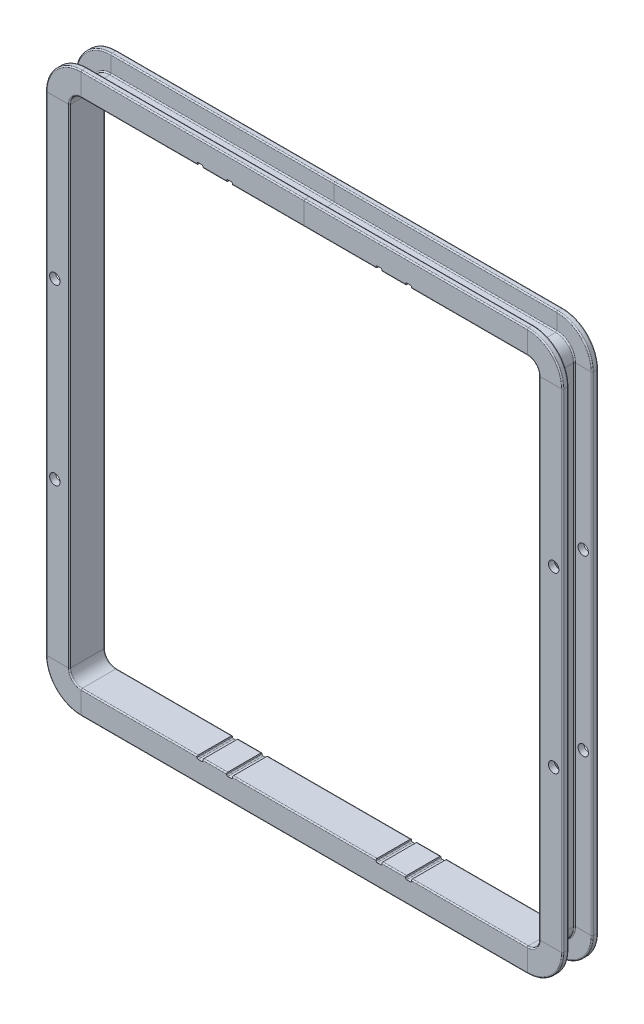
SolidWorks part; units mm, degrees
material "ABS"
ref_plane "Front Plane" through (0, 0, 0) normal (0, 0, 1) x (1, 0, 0)
ref_plane "Top Plane" through (0, 0, 0) normal (0, 1, 0) x (1, 0, 0)
ref_plane "Right Plane" through (0, 0, 0) normal (1, 0, 0) x (0, 0, -1)
sketch "Sketch2" plane through (0, 0, 0) normal (0, 0, 1) x (1, 0, 0)
  line L4 (-886.8198, 967.5698) -> (886.8198, -967.5698) construction
  line L5 (855, 980.75) -> (-855, 980.75)
  line L6 (900, 935.75) -> (900, -935.75)
  line L7 (855, -980.75) -> (-855, -980.75)
  line L8 (-900, 935.75) -> (-900, -935.75)
  line L9 (-886.8198, -967.5698) -> (886.8198, 967.5698) construction
  arc A0 (-855, -980.75) -> (-900, -935.75) centre (-855, -935.75) cw
  arc A1 (900, -935.75) -> (855, -980.75) centre (855, -935.75) cw
  arc A2 (855, 980.75) -> (900, 935.75) centre (855, 935.75) cw
  arc A3 (-855, 980.75) -> (-900, 935.75) centre (-855, 935.75) ccw
  point P0 (0, 0)
  point P18 (0, 0)
  point P20 (855, 980.75)
  dimension "D2" = 45
  dimension "D3" = 1800
  dimension "D1" = 1961.5
sketch "Sketch3" plane through (0, 0, 0) normal (1, 0, 0) x (0, 0, -1)
  line L1 (0, 980.75) -> (0, 935.75) construction
  line L2 (-63.525, 980.75) -> (63.525, 980.75)
  line L3 (68.0625, 985.2875) -> (68.0625, 1066.9625)
  line L5 (-45.375, 1066.9625) -> (-45.375, 1007.975)
  line L6 (-40.8375, 1003.4375) -> (40.8375, 1003.4375)
  line L7 (45.375, 1007.975) -> (45.375, 1066.9625)
  line L9 (-68.0625, 1066.9625) -> (-68.0625, 985.2875)
  line L10 (-49.9125, 1071.5) -> (-63.525, 1071.5)
  line L11 (49.9125, 1071.5) -> (63.525, 1071.5)
  arc A0 (-63.525, 980.75) -> (-68.0625, 985.2875) centre (-63.525, 985.2875) cw
  arc A1 (63.525, 980.75) -> (68.0625, 985.2875) centre (63.525, 985.2875) ccw
  arc A2 (68.0625, 1066.9625) -> (63.525, 1071.5) centre (63.525, 1066.9625) ccw
  arc A3 (45.375, 1066.9625) -> (49.9125, 1071.5) centre (49.9125, 1066.9625) cw
  arc A4 (40.8375, 1003.4375) -> (45.375, 1007.975) centre (40.8375, 1007.975) ccw
  arc A5 (-45.375, 1007.975) -> (-40.8375, 1003.4375) centre (-40.8375, 1007.975) ccw
  arc A6 (-49.9125, 1071.5) -> (-45.375, 1066.9625) centre (-49.9125, 1066.9625) cw
  arc A7 (-63.525, 1071.5) -> (-68.0625, 1066.9625) centre (-63.525, 1066.9625) ccw
  point P0 (0, 980.75)
  point P11 (0, 980.75)
  point P23 (68.0625, 980.75)
  point P26 (68.0625, 1071.5)
  point P29 (45.375, 1071.5)
  point P32 (45.375, 1003.4375)
  point P35 (-45.375, 1003.4375)
  dimension "D5" = 4.5375
  dimension "D2" = 22.6875
  dimension "D1" = 90.75
  dimension "D3" = 22.6875
  dimension "D4" = 90.75
sweep "Sweep1" add profiles "Sketch3" path "Sketch2"
sketch "Sketch5" plane through (0, 0, 0) normal (0, 0, 1) x (1, 0, 0)
  line L0 (-406.5875, 990.75) -> (-392.975, 990.75)
  line L1 (-1216.9089, 0) -> (1386.2762, 0) construction
  line L2 (-388.4375, 986.2125) -> (-388.4375, -986.2125)
  line L4 (-388.4375, 0) -> (-411.125, 0)
  line L5 (-411.125, -986.2125) -> (-411.125, 986.2125)
  line L6 (-406.5875, 990.75) -> (-406.5875, 855) construction
  line L7 (-392.975, 990.75) -> (-392.975, 855) construction
  line L9 (-406.5875, -990.75) -> (-392.975, -990.75)
  line L10 (-343.0625, 922.6875) -> (-343.0625, 801.5742) construction
  line L11 (-302.225, 922.6875) -> (-383.9, 922.6875) construction
  line L12 (-279.5375, -990.75) -> (-293.15, -990.75)
  line L13 (-275, -986.2125) -> (-275, 986.2125)
  line L14 (-297.6875, 0) -> (-275, 0)
  line L15 (-297.6875, 986.2125) -> (-297.6875, -986.2125)
  line L16 (-279.5375, 990.75) -> (-293.15, 990.75)
  line L17 (0, 1301.3162) -> (0, -1456.5953) construction
  line L18 (-406.5875, 990.75) -> (-392.975, 990.75)
  line L19 (-388.4375, 986.2125) -> (-388.4375, -986.2125)
  line L20 (-388.4375, 0) -> (-411.125, 0)
  line L21 (-411.125, -986.2125) -> (-411.125, 986.2125)
  line L22 (-406.5875, -990.75) -> (-392.975, -990.75)
  line L23 (-279.5375, -990.75) -> (-293.15, -990.75)
  line L24 (-275, -986.2125) -> (-275, 986.2125)
  line L25 (-297.6875, 0) -> (-275, 0)
  line L26 (-297.6875, 986.2125) -> (-297.6875, -986.2125)
  line L27 (-279.5375, 990.75) -> (-293.15, 990.75)
  line L28 (343.0625, 922.6875) -> (343.0625, 801.5742) construction
  line L29 (279.5375, 990.75) -> (293.15, 990.75)
  line L30 (297.6875, 986.2125) -> (297.6875, -986.2125)
  line L31 (297.6875, 0) -> (275, 0)
  line L32 (275, -986.2125) -> (275, 986.2125)
  line L33 (279.5375, -990.75) -> (293.15, -990.75)
  line L34 (406.5875, -990.75) -> (392.975, -990.75)
  line L35 (411.125, -986.2125) -> (411.125, 986.2125)
  line L36 (388.4375, 0) -> (411.125, 0)
  line L37 (388.4375, 986.2125) -> (388.4375, -986.2125)
  line L38 (406.5875, 990.75) -> (392.975, 990.75)
  line L39 (279.5375, 990.75) -> (293.15, 990.75)
  line L40 (297.6875, 986.2125) -> (297.6875, -986.2125)
  line L41 (297.6875, 0) -> (275, 0)
  line L42 (275, -986.2125) -> (275, 986.2125)
  line L43 (279.5375, -990.75) -> (293.15, -990.75)
  line L44 (406.5875, -990.75) -> (392.975, -990.75)
  line L45 (411.125, -986.2125) -> (411.125, 986.2125)
  line L46 (388.4375, 0) -> (411.125, 0)
  line L47 (388.4375, 986.2125) -> (388.4375, -986.2125)
  line L48 (406.5875, 990.75) -> (392.975, 990.75)
  line L50 (-855, 980.75) -> (0, 980.75) construction
  arc A0 (-392.975, 990.75) -> (-388.4375, 986.2125) centre (-392.975, 986.2125) cw
  arc A1 (-411.125, 986.2125) -> (-406.5875, 990.75) centre (-406.5875, 986.2125) cw
  arc A2 (-406.5875, 990.75) -> (-411.125, 986.2125) centre (-406.5875, 986.2125) ccw construction
  arc A3 (-411.125, -986.2125) -> (-406.5875, -990.75) centre (-406.5875, -986.2125) ccw
  arc A4 (-392.975, -990.75) -> (-388.4375, -986.2125) centre (-392.975, -986.2125) ccw
  arc A5 (-293.15, -990.75) -> (-297.6875, -986.2125) centre (-293.15, -986.2125) cw
  arc A6 (-275, -986.2125) -> (-279.5375, -990.75) centre (-279.5375, -986.2125) cw
  arc A7 (-275, 986.2125) -> (-279.5375, 990.75) centre (-279.5375, 986.2125) ccw
  arc A8 (-293.15, 990.75) -> (-297.6875, 986.2125) centre (-293.15, 986.2125) ccw
  arc A9 (-392.975, 990.75) -> (-388.4375, 986.2125) centre (-392.975, 986.2125) cw
  arc A10 (-411.125, 986.2125) -> (-406.5875, 990.75) centre (-406.5875, 986.2125) cw
  arc A11 (-411.125, -986.2125) -> (-406.5875, -990.75) centre (-406.5875, -986.2125) ccw
  arc A12 (-392.975, -990.75) -> (-388.4375, -986.2125) centre (-392.975, -986.2125) ccw
  arc A13 (-293.15, -990.75) -> (-297.6875, -986.2125) centre (-293.15, -986.2125) cw
  arc A14 (-275, -986.2125) -> (-279.5375, -990.75) centre (-279.5375, -986.2125) cw
  arc A15 (-275, 986.2125) -> (-279.5375, 990.75) centre (-279.5375, 986.2125) ccw
  arc A16 (-293.15, 990.75) -> (-297.6875, 986.2125) centre (-293.15, 986.2125) ccw
  arc A17 (293.15, 990.75) -> (297.6875, 986.2125) centre (293.15, 986.2125) cw
  arc A18 (275, 986.2125) -> (279.5375, 990.75) centre (279.5375, 986.2125) cw
  arc A19 (275, -986.2125) -> (279.5375, -990.75) centre (279.5375, -986.2125) ccw
  arc A20 (293.15, -990.75) -> (297.6875, -986.2125) centre (293.15, -986.2125) ccw
  arc A21 (392.975, -990.75) -> (388.4375, -986.2125) centre (392.975, -986.2125) cw
  arc A22 (411.125, -986.2125) -> (406.5875, -990.75) centre (406.5875, -986.2125) cw
  arc A23 (411.125, 986.2125) -> (406.5875, 990.75) centre (406.5875, 986.2125) ccw
  arc A24 (392.975, 990.75) -> (388.4375, 986.2125) centre (392.975, 986.2125) ccw
  arc A25 (293.15, 990.75) -> (297.6875, 986.2125) centre (293.15, 986.2125) cw
  arc A26 (275, 986.2125) -> (279.5375, 990.75) centre (279.5375, 986.2125) cw
  arc A27 (275, -986.2125) -> (279.5375, -990.75) centre (279.5375, -986.2125) ccw
  arc A28 (293.15, -990.75) -> (297.6875, -986.2125) centre (293.15, -986.2125) ccw
  arc A29 (392.975, -990.75) -> (388.4375, -986.2125) centre (392.975, -986.2125) cw
  arc A30 (411.125, -986.2125) -> (406.5875, -990.75) centre (406.5875, -986.2125) cw
  arc A31 (411.125, 986.2125) -> (406.5875, 990.75) centre (406.5875, 986.2125) ccw
  arc A32 (392.975, 990.75) -> (388.4375, 986.2125) centre (392.975, 986.2125) ccw
  dimension "D1" = 10
extrude "Cut-Extrude1" cut sketch "Sketch5" against normal through all both and the other way through all contours A1 L5 L4 L2 A0 L0 | L16 A8 L15 L14 L13 A7 | A18 L32 L31 L30 A17 L29 | L38 A24 L37 L36 L35 A23 | A6 L13 L14 L15 A5 L12 | L9 A4 L2 L4 L5 A3 | L33 A20 L30 L31 L32 A19 | A22 L35 L36 L37 A21 L34
sketch "Sketch6" plane through (0, 391.375, 0) normal (0, 1, 0) x (1, 0, 0)
  line L1 (986.2125, -45.375) -> (855, -45.375) construction
  line L2 (922.6875, 40.8375) -> (922.6875, -40.8375) construction
  line L3 (855, 45.375) -> (986.2125, 45.375) construction
  line L6 (986.2125, -45.375) -> (927.225, -45.375)
  line L7 (922.6875, 40.8375) -> (922.6875, -40.8375)
  line L8 (927.225, 45.375) -> (986.2125, 45.375)
  line L10 (990.75, 49.9125) -> (990.75, -49.9125)
  arc A0 (990.75, -49.9125) -> (986.2125, -45.375) centre (986.2125, -49.9125) ccw construction
  arc A1 (922.6875, -40.8375) -> (927.225, -45.375) centre (927.225, -40.8375) ccw construction
  arc A2 (927.225, 45.375) -> (922.6875, 40.8375) centre (927.225, 40.8375) ccw construction
  arc A3 (986.2125, 45.375) -> (990.75, 49.9125) centre (986.2125, 49.9125) ccw construction
  arc A4 (990.75, -49.9125) -> (986.2125, -45.375) centre (986.2125, -49.9125) ccw
  arc A5 (922.6875, -40.8375) -> (927.225, -45.375) centre (927.225, -40.8375) ccw
  arc A6 (927.225, 45.375) -> (922.6875, 40.8375) centre (927.225, 40.8375) ccw
  arc A7 (986.2125, 45.375) -> (990.75, 49.9125) centre (986.2125, 49.9125) ccw
ref_plane "Plane1" through (0, 386.8375, 0) normal (0, -1, 0) x (0, 0, -1)
sketch "Sketch9" plane through (0, 386.8375, 0) normal (0, -1, 0) x (0, 0, -1)
  line L0 (-45.375, 955.75) -> (45.375, 955.75)
  line L4 (45.375, 927.225) -> (45.375, 986.2125)
  line L5 (-40.8375, 922.6875) -> (40.8375, 922.6875)
  line L6 (-45.375, 986.2125) -> (-45.375, 927.225)
  line L7 (49.9125, 990.75) -> (-49.9125, 990.75)
  line L8 (45.375, 955.75) -> (45.375, 986.2125)
  line L10 (-45.375, 986.2125) -> (-45.375, 955.75)
  line L11 (49.9125, 990.75) -> (-49.9125, 990.75)
  line L12 (40.8375, 922.6875) -> (-40.8375, 922.6875) construction
  arc A4 (40.8375, 922.6875) -> (45.375, 927.225) centre (40.8375, 927.225) ccw
  arc A5 (-45.375, 927.225) -> (-40.8375, 922.6875) centre (-40.8375, 927.225) ccw
  arc A6 (-45.375, 986.2125) -> (-49.9125, 990.75) centre (-49.9125, 986.2125) ccw
  arc A7 (49.9125, 990.75) -> (45.375, 986.2125) centre (49.9125, 986.2125) ccw
  arc A10 (-45.375, 986.2125) -> (-49.9125, 990.75) centre (-49.9125, 986.2125) ccw
  arc A11 (49.9125, 990.75) -> (45.375, 986.2125) centre (49.9125, 986.2125) ccw
  dimension "D2" = 33.0625
  dimension "D1" = 0
extrude "Boss-Extrude1" [suppressed] add sketch "Sketch9" along normal blind 250
ref_plane "Plane2" through (0, 401.5, 0) normal (0, 1, 0) x (1, 0, 0)
sketch "Sketch11" plane through (0, 401.5, 0) normal (0, 1, 0) x (1, 0, 0)
  line L4 (955.75, 45.375) -> (955.75, -45.375)
  line L5 (986.2125, 45.375) -> (955.75, 45.375)
  line L6 (990.75, -49.9125) -> (990.75, 49.9125)
  line L7 (955.75, -45.375) -> (986.2125, -45.375)
  line L8 (955.75, 45.375) -> (955.75, -45.375)
  line L9 (986.2125, 45.375) -> (955.75, 45.375)
  line L10 (990.75, -49.9125) -> (990.75, 49.9125)
  line L11 (955.75, -45.375) -> (986.2125, -45.375)
  arc A2 (986.2125, 45.375) -> (990.75, 49.9125) centre (986.2125, 49.9125) ccw
  arc A3 (990.75, -49.9125) -> (986.2125, -45.375) centre (986.2125, -49.9125) ccw
  arc A4 (986.2125, 45.375) -> (990.75, 49.9125) centre (986.2125, 49.9125) ccw
  arc A5 (990.75, -49.9125) -> (986.2125, -45.375) centre (986.2125, -49.9125) ccw
  dimension "D1" = 0
extrude "Boss-Extrude2" [suppressed] add sketch "Sketch11" against normal blind 250
sketch "Sketch10" plane through (0, 0, -68.0625) normal (0, 0, -1) x (-1, 0, 0)
  line L0 (-411.125, 980.75) -> (-855, 980.75) construction
  line L1 (-929.5375, 330.75) -> (-1071.4036, 330.75)
  line L2 (-929.5375, 330.75) -> (-929.5375, 278.75)
  line L3 (-929.5375, 278.75) -> (-1071.4036, 278.75)
  line L4 (-1071.4036, 330.75) -> (-1071.4036, 278.75)
  line L5 (-904.5375, 935.75) -> (-904.5375, -935.75) construction
  point P8 (-929.5375, 304.75)
  dimension "D1" = 650
  dimension "D2" = 25
  dimension "D3" = 52
  dimension "D4" = 141.8661
extrude "Cut-Extrude2" [suppressed] cut sketch "Sketch10" against normal blind 50
sketch "Sketch12" [suppressed] plane through (990.75, 0, 0) normal (1, 0, 0) x (0, 0, -1)
  line L0 (0, 330.75) -> (0, 205.75) construction
  line L1 (26, 330.75) -> (26, 205.75)
  line L2 (-26, 330.75) -> (-26, 205.75)
  line L3 (63.525, 330.75) -> (49.9125, 330.75) construction
  arc A0 (26, 330.75) -> (-26, 330.75) centre (0, 330.75) ccw
  arc A1 (-26, 205.75) -> (26, 205.75) centre (0, 205.75) ccw
  point P3 (0, 268.25)
  dimension "D1" = 26
  dimension "D2" = 125
extrude "Cut-Extrude3" [suppressed] cut sketch "Sketch12" against normal up to surface (35 mm away)
fillet "Fillet1" [suppressed] radius 10
sketch "Sketch13" plane through (0, 0, 68.0625) normal (0, 0, 1) x (1, 0, 0)
  line L0 (0, 1444.483) -> (0, -1157.2437) construction
  line L1 (-855, 980.75) -> (-411.125, 980.75) construction
  line L3 (-411.125, -985.2875) -> (-855, -985.2875) construction
  line L5 (-986.2125, -935.75) -> (-986.2125, 935.75) construction
  circle A0 centre (-956.2125, 330.75) radius 20
  circle A1 centre (-956.2125, -335.2875) radius 20
  circle A2 centre (956.2125, -335.2875) radius 20
  circle A3 centre (956.2125, 330.75) radius 20
  dimension "D3" = 40
  dimension "D1" = 650
  dimension "D2" = 650
  dimension "D4" = 30
extrude "Cut-Extrude4" cut sketch "Sketch13" against normal through all both and the other way through all
equation "\"A\"= 1.8'Coil Case Length"
equation "\"D2@Sketch2\"=\"A\"/40"
equation "\"B\"= 82.5mm * 1.1'20 AWG Diam*100"
equation "\"D5@Sketch3\"=\"B\"/20"
equation "\"D2@Sketch3\"=\"B\"/4"
equation "\"D1@Sketch3\"=\"B\""
equation "\"D3@Sketch3\"=\"B\"/4"
equation "\"C\"= \"A\" + \"B\" * 2 - .02"
equation "\"D3@Sketch2\"=\"A\""
equation "\"D1@Sketch2\"=\"C\""
equation "\"D4@Sketch3\"=\"B\""
